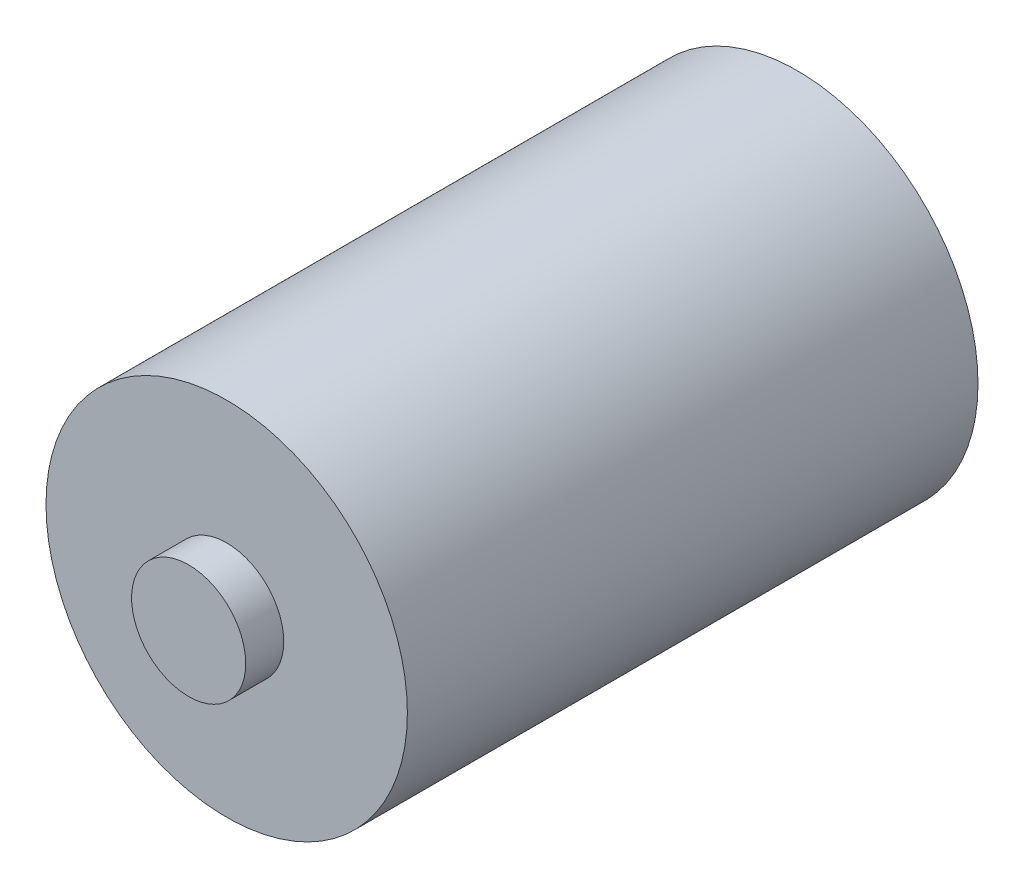
SolidWorks part; units mm, degrees
ref_plane "Front Plane" through (0, 0, 0) normal (0, 0, 1) x (1, 0, 0)
ref_plane "Top Plane" through (0, 0, 0) normal (0, 1, 0) x (1, 0, 0)
ref_plane "Right Plane" through (0, 0, 0) normal (1, 0, 0) x (0, 0, -1)
sketch "Sketch1" plane through (0, 0, 0) normal (0, 0, 1) x (1, 0, 0)
  circle A0 centre (0, 0) radius 47.5
  dimension "D1" = 95
extrude "Boss-Extrude1" add sketch "Sketch1" along normal mid plane 150
sketch "Sketch2" plane through (0, 0, 75) normal (0, 0, 1) x (1, 0, 0)
  circle A0 centre (0, 0) radius 15
  dimension "D1" = 30
extrude "Boss-Extrude2" add sketch "Sketch2" along normal blind 10 and the other way blind 160
